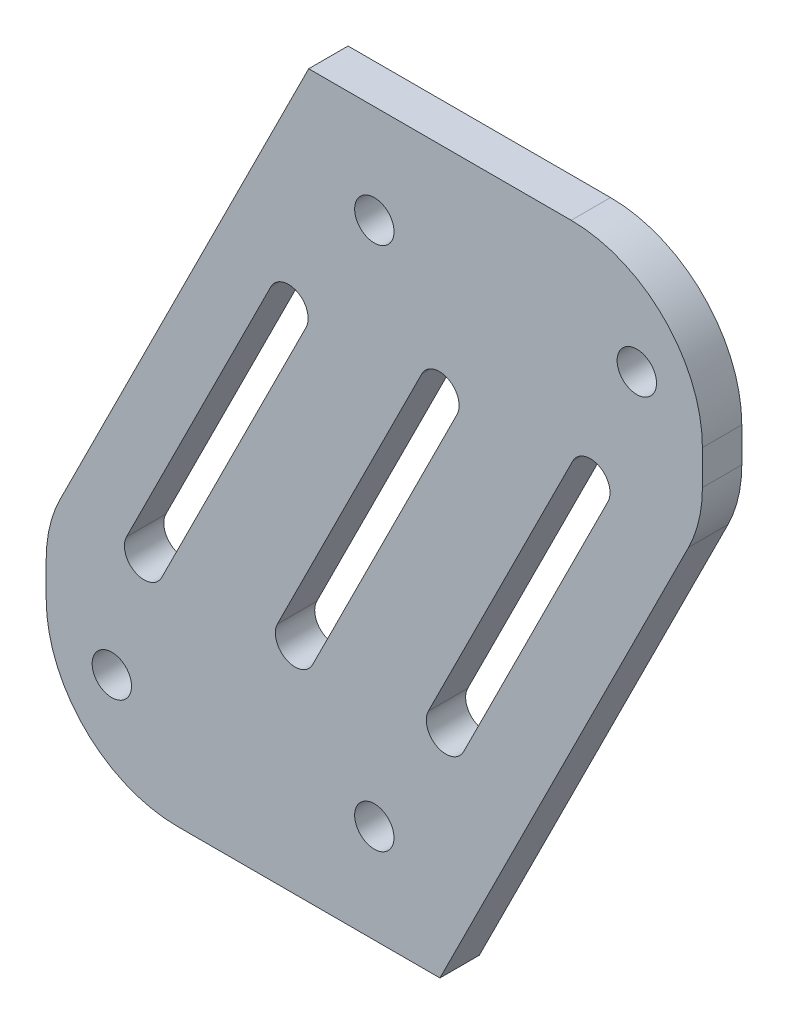
SolidWorks part; units mm, degrees
material "Thornel Mat VMA"
ref_plane "前视基准面" through (0, 0, 0) normal (0, 0, 1) x (1, 0, 0)
ref_plane "上视基准面" through (0, 0, 0) normal (0, 1, 0) x (1, 0, 0)
ref_plane "右视基准面" through (0, 0, 0) normal (1, 0, 0) x (0, 0, -1)
sketch "草图2" plane through (0, 0, 0) normal (0, 0, 1) x (1, 0, 0)
  line L0 (0, 0) -> (0, 15)
  line L1 (0, 15) -> (-30, 15)
  line L2 (-30, 15) -> (-50, -25)
  line L3 (-50, -25) -> (-50, -40)
  line L4 (-50, -40) -> (-20, -40)
  line L5 (-20, -40) -> (0, 0)
  dimension "D1" = 15
  dimension "D2" = 15
  dimension "D3" = 30
  dimension "D4" = 10
  dimension "D5" = 25
extrude "凸台-拉伸1" add sketch "草图2" along normal blind 3
sketch "草图3" plane through (0, 0, 3) normal (0, 0, 1) x (1, 0, 0)
  line L0 (0, 7.5) -> (-33.75, 7.5) construction
  line L1 (0, 0) -> (0, 15) construction
  line L2 (-30, 15) -> (-50, -25) construction
  line L3 (-50, -32.5) -> (-16.25, -32.5) construction
  line L4 (-50, -25) -> (-50, -40) construction
  line L5 (-20, -40) -> (0, 0) construction
  circle A0 centre (-5, 7.5) radius 1.5
  circle A1 centre (-25, 7.5) radius 1.5
  circle A2 centre (-45, -32.5) radius 1.5
  circle A3 centre (-25, -32.5) radius 1.5
  dimension "D1" = 5
  dimension "D2" = 3
  dimension "D3" = 20
  dimension "D4" = 5
  dimension "D5" = 20
extrude "切除-拉伸1" cut sketch "草图3" against normal through all
fillet "圆角2" radius 10 2 edges at (-50, -25, 1.5) (0, 0, 1.5)
fillet "圆角3" radius 10 2 edges at (-50, -40, 1.5) (0, 15, 1.5)
sketch "草图7" plane through (0, 0, 3) normal (0, 0, 1) x (1, 0, 0)
  line L0 (-42.5418, -23.5) -> (-31.5418, -1.5) construction
  line L1 (-43.8834, -22.8292) -> (-32.8834, -0.8292)
  line L2 (-41.2002, -24.1708) -> (-30.2002, -2.1708)
  line L3 (-30, 15) -> (-48.9443, -22.8885) construction
  line L4 (-40, -40) -> (-20, -40) construction
  line L5 (-10, 15) -> (-30, 15) construction
  line L6 (-29.7002, -24.1708) -> (-18.7002, -2.1708)
  line L7 (-32.3834, -22.8292) -> (-21.3834, -0.8292)
  line L8 (-31.0418, -23.5) -> (-20.0418, -1.5) construction
  line L9 (-18.2002, -24.1708) -> (-7.2002, -2.1708)
  line L10 (-20.8834, -22.8292) -> (-9.8834, -0.8292)
  line L11 (-19.5418, -23.5) -> (-8.5418, -1.5) construction
  arc A0 (-43.8834, -22.8292) -> (-41.2002, -24.1708) centre (-42.5418, -23.5) ccw
  arc A1 (-30.2002, -2.1708) -> (-32.8834, -0.8292) centre (-31.5418, -1.5) ccw
  arc A2 (-32.3834, -22.8292) -> (-29.7002, -24.1708) centre (-31.0418, -23.5) ccw
  arc A3 (-18.7002, -2.1708) -> (-21.3834, -0.8292) centre (-20.0418, -1.5) ccw
  arc A4 (-20.8834, -22.8292) -> (-18.2002, -24.1708) centre (-19.5418, -23.5) ccw
  arc A5 (-7.2002, -2.1708) -> (-9.8834, -0.8292) centre (-8.5418, -1.5) ccw
  point P2 (-37.0418, -12.5)
  point P17 (-25.5418, -12.5)
  point P24 (-14.0418, -12.5)
  dimension "D4" = 1.5
  dimension "D1" = 6
  dimension "D2" = 16.5
  dimension "D3" = 16.5
  dimension "D5" = 3
extrude "切除-拉伸3" cut sketch "草图7" against normal through all
